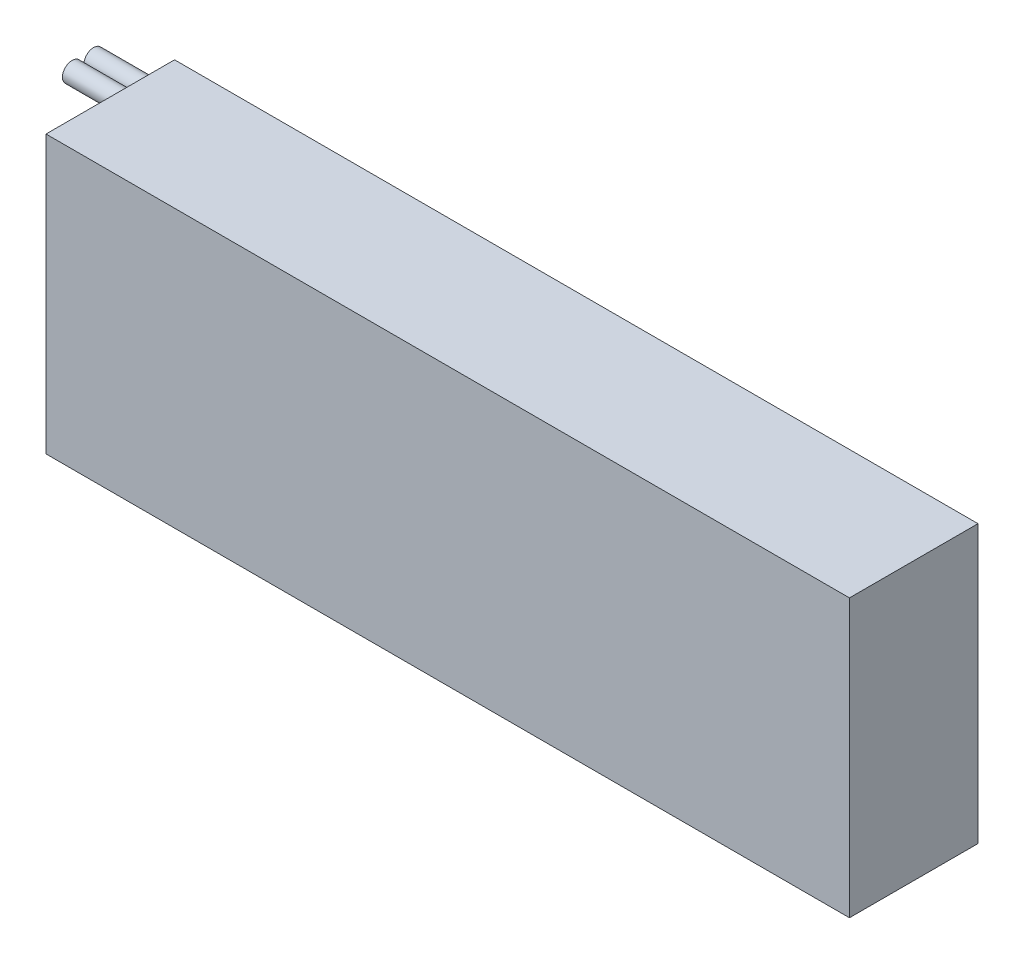
SolidWorks part; units mm, degrees
ref_plane "Front Plane" through (0, 0, 0) normal (0, 0, 1) x (1, 0, 0)
ref_plane "Top Plane" through (0, 0, 0) normal (0, 1, 0) x (1, 0, 0)
ref_plane "Right Plane" through (0, 0, 0) normal (1, 0, 0) x (0, 0, -1)
sketch "Sketch1" plane through (0, 0, 0) normal (0, 0, 1) x (1, 0, 0)
  line L1 (-112.1292, 36.0222) -> (32.8708, 36.0222)
  line L2 (-112.1292, 36.0222) -> (-112.1292, -13.9778)
  line L3 (-112.1292, -13.9778) -> (32.8708, -13.9778)
  line L4 (32.8708, 36.0222) -> (32.8708, -13.9778)
  dimension "D1" = 145
  dimension "D2" = 50
extrude "Boss-Extrude1" add sketch "Sketch1" along normal blind 23.2
sketch "Sketch2" plane through (-112.1292, 0, 0) normal (-1, 0, 0) x (0, 0, 1)
  circle A0 centre (4.6116, 33.4942) radius 1.75
  dimension "D1" = 3.5
extrude "Boss-Extrude2" add sketch "Sketch2" along normal blind 10
sketch "Sketch3" plane through (-112.1292, 0, 0) normal (-1, 0, 0) x (0, 0, 1)
  circle A0 centre (8.4875, 33.4219) radius 1.75
  dimension "D1" = 3.5
extrude "Boss-Extrude3" add sketch "Sketch3" along normal blind 10
